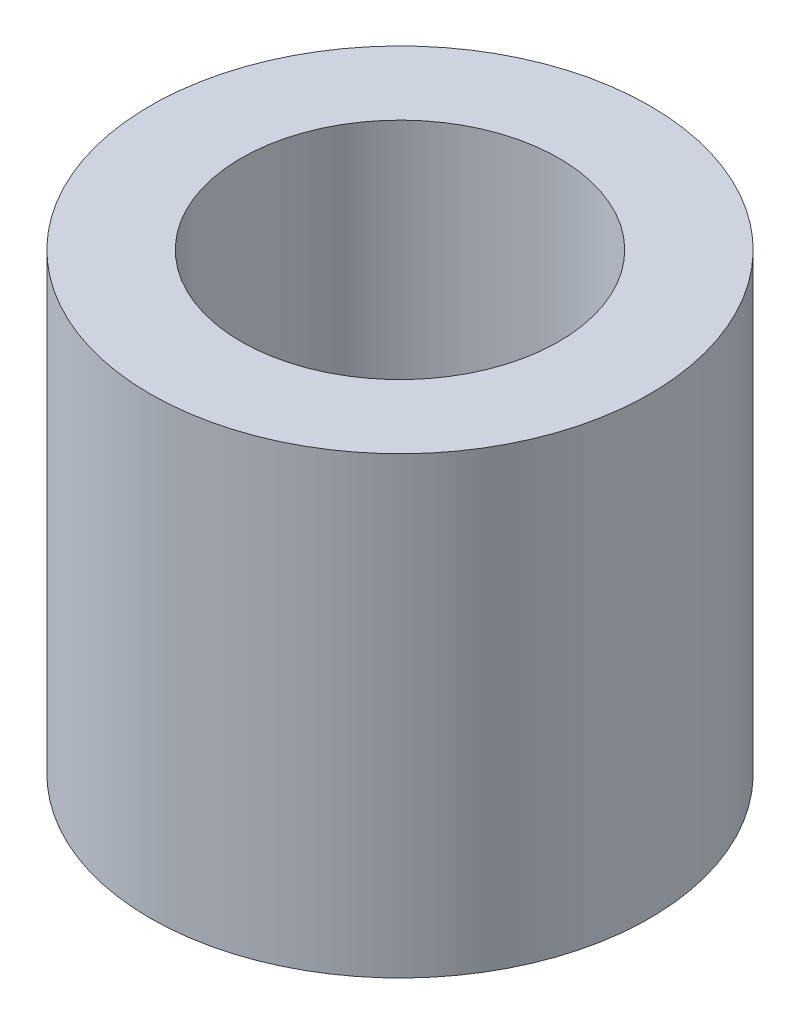
SolidWorks part; units mm, degrees
ref_plane "Front Plane" through (0, 0, 0) normal (0, 0, 1) x (1, 0, 0)
ref_plane "Top Plane" through (0, 0, 0) normal (0, 1, 0) x (1, 0, 0)
ref_plane "Right Plane" through (0, 0, 0) normal (1, 0, 0) x (0, 0, -1)
sketch "Sketch1" plane through (0, 0, 0) normal (0, 1, 0) x (1, 0, 0)
  circle A0 centre (0, 0) radius 1.75
  circle A1 centre (0, 0) radius 2.75
  dimension "D1" = 3.5
  dimension "D2" = 1
extrude "Boss-Extrude1" add sketch "Sketch1" along normal blind 5
